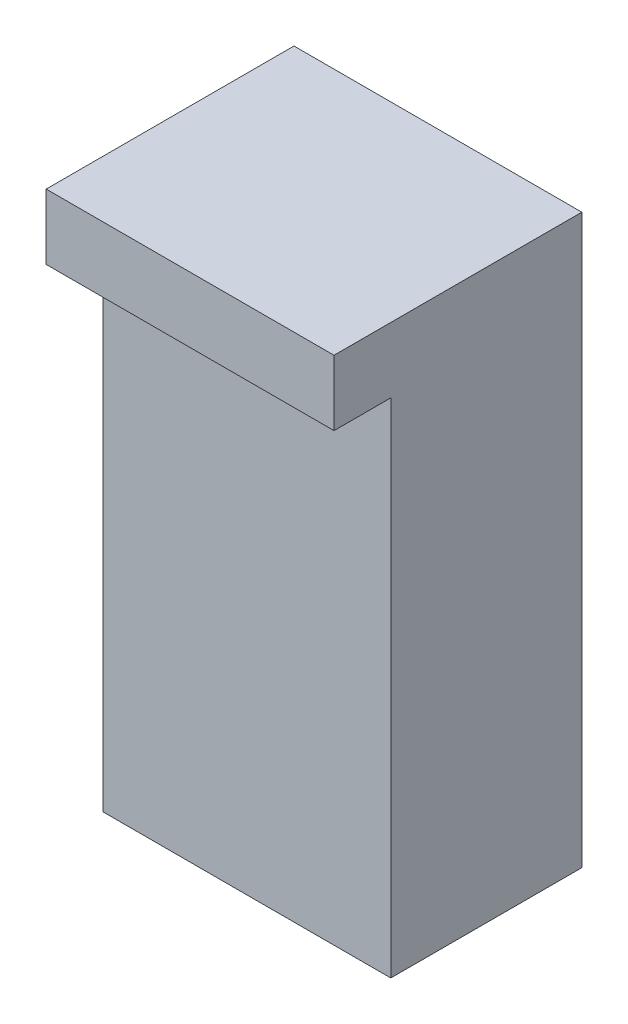
SolidWorks part; units mm, degrees
ref_plane "Front Plane" through (0, 0, 0) normal (0, 0, 1) x (1, 0, 0)
ref_plane "Top Plane" through (0, 0, 0) normal (0, 1, 0) x (1, 0, 0)
ref_plane "Right Plane" through (0, 0, 0) normal (1, 0, 0) x (0, 0, -1)
sketch "Sketch1" plane through (0, 0, 0) normal (0, 1, 0) x (1, 0, 0)
  line L1 (12.8778, -8.5471) -> (-12.8778, -8.5471)
  line L2 (12.8778, -8.5471) -> (12.8778, 8.5471)
  line L3 (12.8778, 8.5471) -> (-12.8778, 8.5471)
  line L4 (-12.8778, -8.5471) -> (-12.8778, 8.5471)
  line L5 (12.8778, -8.5471) -> (-12.8778, 8.5471) construction
  line L6 (12.8778, 8.5471) -> (-12.8778, -8.5471) construction
  point P0 (0, 0)
  dimension "D1" = 17.0942
  dimension "D2" = 25.7556
extrude "Boss-Extrude1" add sketch "Sketch1" along normal blind 50.8
sketch "Sketch2" plane through (0, 0, 8.5471) normal (0, 0, 1) x (1, 0, 0)
  line L0 (12.8778, 50.8) -> (12.8778, 0) construction
  line L1 (-12.8778, 50.8) -> (12.8778, 50.8)
  line L2 (-12.8778, 50.8) -> (-12.8778, 44.958)
  line L3 (-12.8778, 44.958) -> (12.8778, 44.958)
  line L4 (12.8778, 50.8) -> (12.8778, 44.958)
  line L5 (-12.8778, 50.8) -> (-12.8778, 0) construction
  line L6 (-12.8778, 50.8) -> (-12.8778, 0)
  line M4 (12.8778, 0) -> (12.8778, 50.8)
  line M5 (12.8778, 50.8) -> (-12.8778, 50.8)
  line M6 (-12.8778, 50.8) -> (-12.8778, 0)
  dimension "D1" = 5.842
  dimension "D2" = 50.8
extrude "Boss-Extrude2" add sketch "Sketch2" along normal blind 5.08 contours L3 M6 M4 M5
